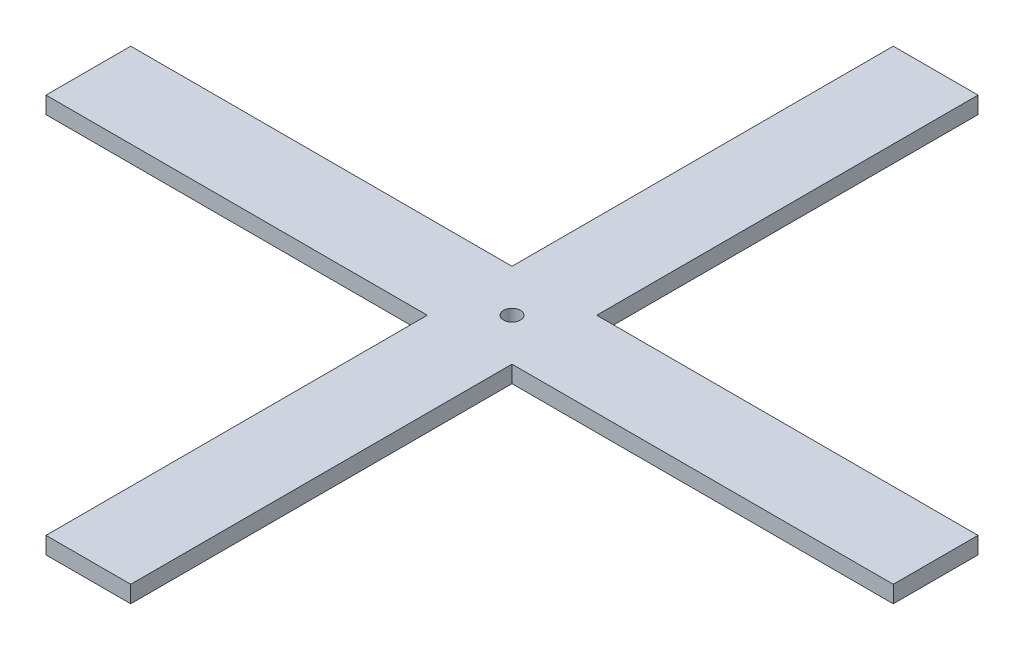
SolidWorks part; units mm, degrees
ref_plane "Front Plane" through (0, 0, 0) normal (0, 0, 1) x (1, 0, 0)
ref_plane "Top Plane" through (0, 0, 0) normal (0, 1, 0) x (1, 0, 0)
ref_plane "Right Plane" through (0, 0, 0) normal (1, 0, 0) x (0, 0, -1)
sketch "Sketch1" plane through (0, 0, 0) normal (0, 1, 0) x (1, 0, 0)
  line L1 (-250, -25) -> (250, -25)
  line L2 (-250, -25) -> (-250, 25)
  line L3 (-250, 25) -> (250, 25)
  line L4 (250, -25) -> (250, 25)
  line L5 (-250, -25) -> (250, 25) construction
  line L6 (-250, 25) -> (250, -25) construction
  point P0 (0, 0)
  dimension "D1" = 50
  dimension "D2" = 500
extrude "Boss-Extrude1" add sketch "Sketch1" along normal blind 10
sketch "Sketch2" plane through (0, 0, 0) normal (0, 1, 0) x (1, 0, 0)
  line L1 (-25, -250) -> (25, -250)
  line L2 (-25, -250) -> (-25, 250)
  line L3 (-25, 250) -> (25, 250)
  line L4 (25, -250) -> (25, 250)
  line L5 (-25, -250) -> (25, 250) construction
  line L6 (-25, 250) -> (25, -250) construction
  point P0 (0, 0)
  dimension "D1" = 500
  dimension "D2" = 50
extrude "Boss-Extrude2" add sketch "Sketch2" along normal blind 10
sketch "Sketch3" plane through (0, 10, 0) normal (0, 1, 0) x (1, 0, 0)
  circle A0 centre (0, 0) radius 5
  dimension "D1" = 10
extrude "Cut-Extrude1" cut sketch "Sketch3" against normal through all both and the other way through all
